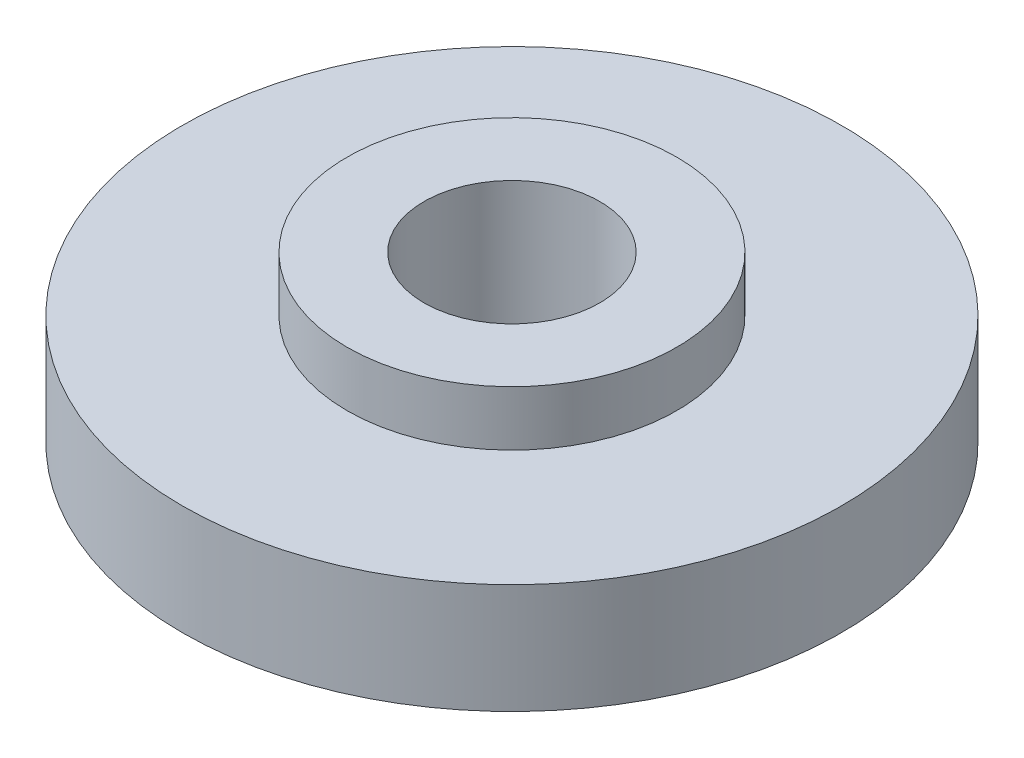
SolidWorks part; units mm, degrees
ref_plane "Front Plane" through (0, 0, 0) normal (0, 0, 1) x (1, 0, 0)
ref_plane "Top Plane" through (0, 0, 0) normal (0, 1, 0) x (1, 0, 0)
ref_plane "Right Plane" through (0, 0, 0) normal (1, 0, 0) x (0, 0, -1)
sketch "Sketch1" plane through (0, 0, 0) normal (0, 1, 0) x (1, 0, 0)
  circle A0 centre (0, 0) radius 6
  dimension "D1" = 12
extrude "Boss-Extrude1" add sketch "Sketch1" along normal blind 2
sketch "Sketch2" plane through (0, 2, 0) normal (0, 1, 0) x (1, 0, 0)
  circle A0 centre (0, 0) radius 3
extrude "Boss-Extrude2" add sketch "Sketch2" along normal blind 1
sketch "Sketch3" plane through (0, 3, 0) normal (0, 1, 0) x (1, 0, 0)
  circle A0 centre (0, 0) radius 1.6
extrude "Cut-Extrude1" cut sketch "Sketch3" against normal blind 6
